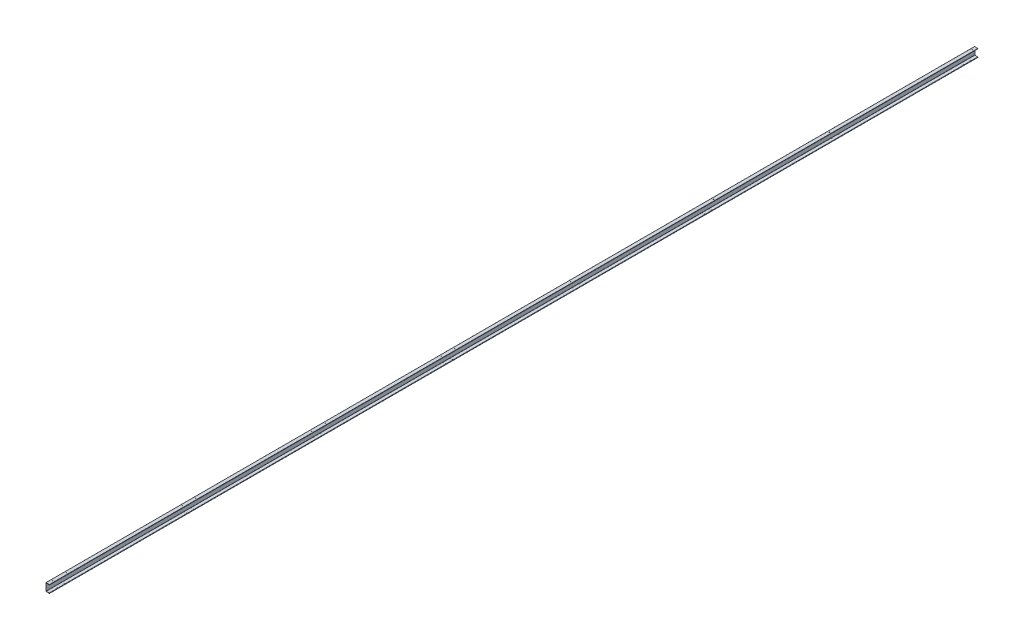
SolidWorks part; units mm, degrees
material "Gray Cast Iron"
ref_plane "Front Plane" through (0, 0, 0) normal (0, 0, 1) x (1, 0, 0)
ref_plane "Top Plane" through (0, 0, 0) normal (0, 1, 0) x (1, 0, 0)
ref_plane "Right Plane" through (0, 0, 0) normal (1, 0, 0) x (0, 0, -1)
sketch "Sketch1" plane through (0, 0, 0) normal (0, 0, 1) x (1, 0, 0)
  line L0 (0, 50) -> (0, -50)
  line L1 (0, -50) -> (45, -50)
  line L2 (0, 50) -> (45, 50)
  line L3 (45, 50) -> (45, 44.9)
  line L4 (45, 44.9) -> (3, 44.9)
  line L5 (45, -50) -> (45, -44.9)
  line L6 (45, -44.9) -> (3, -44.9)
  line L7 (3, -44.9) -> (3, 44.9)
  point P4 (0, 0)
  dimension "D1" = 100
  dimension "D2" = 45
  dimension "D3" = 45
  dimension "D4" = 5.1
  dimension "D5" = 42
  dimension "D6" = 89.8
extrude "Boss-Extrude1" add sketch "Sketch1" along normal blind 12000
fillet "Fillet1" radius 3 2 edges at (45, -44.9, 6000) (45, 44.9, 6000)
fillet "Fillet2" radius 1 4 edges at (0, 50, 6000) (0, -50, 6000) (45, -50, 6000) (45, 50, 6000)
fillet "Fillet3" radius 1 2 edges at (3, -44.9, 6000) (3, 44.9, 6000)
sketch "Sketch2" plane through (0, 50, 0) normal (0, 1, 0) x (1, 0, 0)
  line L0 (22.5, 0) -> (22.5, -12000) construction
  line L1 (44, 0) -> (1, 0) construction
  line L2 (44, -12000) -> (1, -12000) construction
  circle A2 centre (22.5, -50) radius 3
  circle A3 centre (22.5, -223) radius 3
  circle A4 centre (22.5, -1723) radius 3
  circle A5 centre (22.5, -1896) radius 3
  circle A6 centre (22.5, -3396) radius 3
  circle A7 centre (22.5, -3569) radius 3
  circle A8 centre (22.5, -5069) radius 3
  circle A9 centre (22.5, -5242) radius 3
  circle A10 centre (22.5, -6742) radius 3
  circle A11 centre (22.5, -6915) radius 3
  circle A12 centre (22.5, -8415) radius 3
  circle A13 centre (22.5, -8588) radius 3
  circle A14 centre (22.5, -10088) radius 3
  circle A15 centre (22.5, -10261) radius 3
  circle A16 centre (22.5, -11761) radius 3
  circle A17 centre (22.5, -11934) radius 3
  dimension "D1" = 173
  dimension "D3" = 6
  dimension "D4" = 50
  dimension "D5" = 173
  dimension "D6" = 6
  dimension "D2" = 1500
  dimension "D7" = 173
  dimension "D8" = 1500
  dimension "D9" = 6
  dimension "D10" = 173
  dimension "D11" = 1500
  dimension "D12" = 6
  dimension "D13" = 173
  dimension "D15" = 6
  dimension "D16" = 173
  dimension "D17" = 1500
  dimension "D18" = 6
  dimension "D19" = 173
  dimension "D20" = 1500
  dimension "D21" = 6
  dimension "D22" = 173
  dimension "D23" = 1500
  dimension "D30" = 6
  dimension "D14" = 1500
extrude "Cut-Extrude2" cut sketch "Sketch2" against normal up to next
sketch "Sketch5" plane through (0, -50, 0) normal (0, -1, 0) x (1, 0, 0)
  line L0 (22.5, 12000) -> (22.5, 0) construction
  line L1 (1, 12000) -> (44, 12000) construction
  line L2 (1, 0) -> (44, 0) construction
  line L3 (44, 10174.4988) -> (1, 10174.4988) construction
  line L4 (44, 0) -> (44, 12000) construction
  line L5 (12.5, 10174.4988) -> (957.5, 10174.4988) construction
  line L6 (1, 12000) -> (1, 0) construction
  line L7 (1, 10124.4988) -> (1, 10224.4988) construction
  line L8 (44, 10224.4988) -> (44, 10124.4988) construction
  line L9 (44, 10124.4988) -> (1, 10124.4988) construction
  line L10 (1, 10224.4988) -> (44, 10224.4988) construction
  line L11 (1, 8501.4988) -> (44, 8501.4988) construction
  line L12 (1, 6828.4988) -> (44, 6828.4988) construction
  line L13 (1, 5155.4988) -> (44, 5155.4988) construction
  line L14 (1, 3482.4988) -> (44, 3482.4988) construction
  line L15 (1, 1809.4988) -> (44, 1809.4988) construction
  line L16 (1, 136.4988) -> (44, 136.4988) construction
  line L17 (1, 11847.4988) -> (44, 11847.4988) construction
  circle A0 centre (7.5, 10219.4988) radius 3
  circle A1 centre (37.5, 10219.4988) radius 3
  circle A2 centre (37.5, 10129.4988) radius 3
  circle A3 centre (7.5, 10129.4988) radius 3
  circle A4 centre (7.5, 8546.4988) radius 3
  circle A5 centre (37.5, 8546.4988) radius 3
  circle A6 centre (37.5, 8456.4988) radius 3
  circle A7 centre (7.5, 8456.4988) radius 3
  circle A8 centre (7.5, 6873.4988) radius 3
  circle A9 centre (37.5, 6873.4988) radius 3
  circle A10 centre (37.5, 6783.4988) radius 3
  circle A11 centre (7.5, 6783.4988) radius 3
  circle A12 centre (7.5, 5200.4988) radius 3
  circle A13 centre (37.5, 5200.4988) radius 3
  circle A14 centre (37.5, 5110.4988) radius 3
  circle A15 centre (7.5, 5110.4988) radius 3
  circle A16 centre (7.5, 3527.4988) radius 3
  circle A17 centre (37.5, 3527.4988) radius 3
  circle A18 centre (37.5, 3437.4988) radius 3
  circle A19 centre (7.5, 3437.4988) radius 3
  circle A20 centre (7.5, 1854.4988) radius 3
  circle A21 centre (37.5, 1854.4988) radius 3
  circle A22 centre (37.5, 1764.4988) radius 3
  circle A23 centre (7.5, 1764.4988) radius 3
  circle A24 centre (7.5, 181.4988) radius 3
  circle A25 centre (37.5, 181.4988) radius 3
  circle A26 centre (37.5, 91.4988) radius 3
  circle A27 centre (7.5, 91.4988) radius 3
  circle A28 centre (7.5, 11892.4988) radius 3
  circle A29 centre (37.5, 11892.4988) radius 3
  circle A30 centre (37.5, 11802.4988) radius 3
  circle A31 centre (7.5, 11802.4988) radius 3
  point P17 (1, 10174.4988)
  dimension "D2" = 5
  dimension "D3" = 5
  dimension "D4" = 6
  dimension "D5" = 15
  dimension "D6" = 15
  dimension "D8" = 45
  dimension "D9" = 6
  dimension "D10" = 45
  dimension "D11" = 15
  dimension "D12" = 15
  dimension "D14" = 45
  dimension "D15" = 45
  dimension "D16" = 30
  dimension "D17" = 6
  dimension "D19" = 45
  dimension "D20" = 45
  dimension "D21" = 30
  dimension "D22" = 6
  dimension "D24" = 45
  dimension "D25" = 45
  dimension "D26" = 6
  dimension "D27" = 30
  dimension "D28" = 15
  dimension "D29" = 15
  dimension "D30" = 15
  dimension "D32" = 45
  dimension "D33" = 45
  dimension "D34" = 6
  dimension "D35" = 15
  dimension "D36" = 30
  dimension "D38" = 45
  dimension "D39" = 45
  dimension "D40" = 15
  dimension "D41" = 30
  dimension "D42" = 6
  dimension "D44" = 45
  dimension "D46" = 15
  dimension "D47" = 30
  dimension "D48" = 6
  dimension "D1" = 100
  dimension "D7" = 1673
  dimension "D13" = 1673
  dimension "D18" = 1673
  dimension "D23" = 1673
  dimension "D31" = 1673
  dimension "D37" = 1673
  dimension "D43" = 1673
  dimension "D45" = 45
extrude "Cut-Extrude4" cut sketch "Sketch5" against normal blind 10
